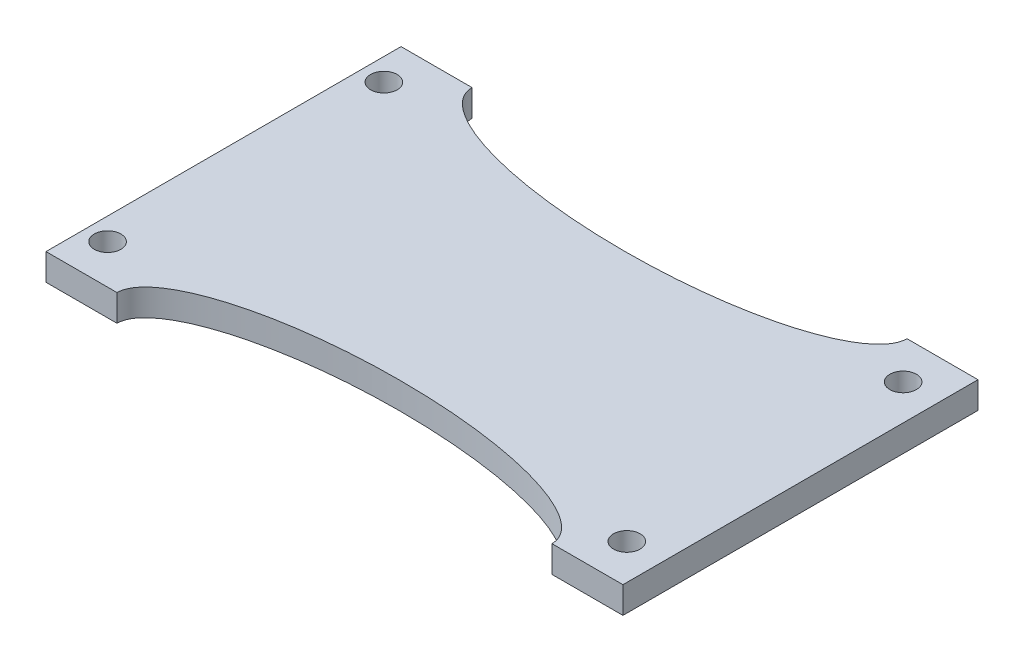
SolidWorks part; units mm, degrees
ref_plane "Plan de face" through (0, 0, 0) normal (0, 0, 1) x (1, 0, 0)
ref_plane "Plan de dessus" through (0, 0, 0) normal (0, 1, 0) x (1, 0, 0)
ref_plane "Plan de droite" through (0, 0, 0) normal (1, 0, 0) x (0, 0, -1)
sketch "Esquisse2" plane through (0, -44.9785, 0) normal (0, -1, 0) x (1, 0, 0)
  line L0 (-80.3673, 78.0906) -> (-114.3778, 78.0906) construction
  line L1 (-80.3673, 58.0906) -> (-88.3673, 58.0906)
  line L2 (-80.3673, 58.0906) -> (-80.3673, 98.0906)
  line L3 (-80.3673, 98.0906) -> (-88.3673, 98.0906)
  line L4 (-145.3673, 58.0906) -> (-145.3673, 98.0906)
  line L5 (-137.3673, 58.0906) -> (-145.3673, 58.0906)
  line L6 (-137.3673, 98.0906) -> (-145.3673, 98.0906)
  ellipse E0 centre (-112.8673, 58.0906) end of major axis (-88.3673, 58.0906) minor radius 7.3806 (-88.3673, 58.0906) -> (-137.3673, 58.0906) ccw
  ellipse E1 centre (-112.8673, 98.0906) end of major axis (-88.3673, 98.0906) minor radius 7.3806 (-88.3673, 98.0906) -> (-137.3673, 98.0906) cw
extrude "Boss.-Extru.1" add sketch "Esquisse2" along normal blind 3
sketch "Esquisse3" plane through (0, -47.9785, 0) normal (0, -1, 0) x (1, 0, 0)
  line L0 (-84.3673, 98.0906) -> (-84.3673, 58.0906) construction
  line L1 (-80.3673, 98.0906) -> (-88.3673, 98.0906) construction
  line L2 (-88.3673, 58.0906) -> (-80.3673, 58.0906) construction
  line L3 (-84.3673, 78.0906) -> (-90.3905, 78.0906) construction
  line L4 (-145.3673, 98.0906) -> (-140.3673, 98.0906) construction
  line L5 (-140.3673, 98.0906) -> (-140.3673, 99.4303) construction
  line L6 (-137.3673, 98.0906) -> (-145.3673, 98.0906) construction
  line L7 (-142.8673, 98.0906) -> (-142.8673, 58.0906) construction
  line L8 (-145.3673, 58.0906) -> (-137.3673, 58.0906) construction
  line L9 (-84.3673, 93.6551) -> (-145.3673, 93.6551) construction
  line L10 (-145.3673, 98.0906) -> (-145.3673, 58.0906) construction
  circle A0 centre (-84.3673, 93.6551) radius 1.5
  circle A1 centre (-84.3673, 62.5261) radius 1.5
  circle A2 centre (-142.8673, 93.6551) radius 1.5
  circle A3 centre (-142.8673, 62.5261) radius 1.5
extrude "Enlèv. mat.-Extru.1" cut sketch "Esquisse3" against normal through all
